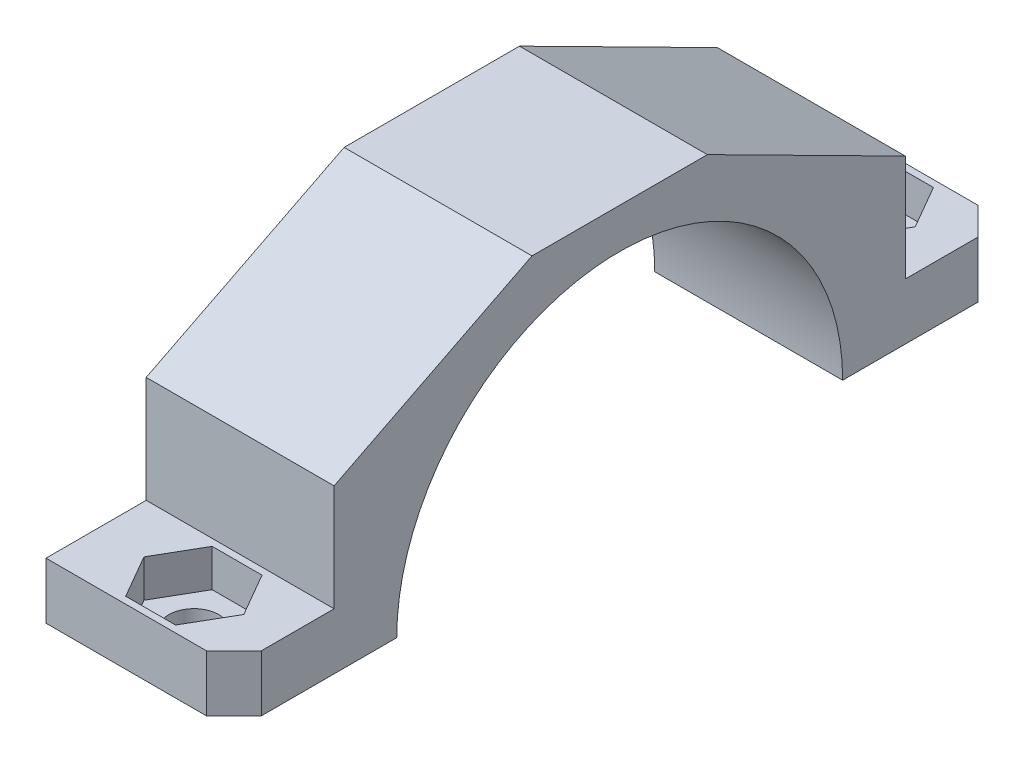
SolidWorks part; units mm, degrees
ref_plane "Front Plane" through (0, 0, 0) normal (0, 0, 1) x (1, 0, 0)
ref_plane "Top Plane" through (0, 0, 0) normal (0, 1, 0) x (1, 0, 0)
ref_plane "Right Plane" through (0, 0, 0) normal (1, 0, 0) x (0, 0, -1)
sketch "Sketch1" plane through (0, 0, 0) normal (1, 0, 0) x (0, 0, -1)
  line L0 (-22.8, 4.5) -> (-22.8, 13)
  line L1 (-22.8, 13) -> (-7, 21)
  line L2 (-7, 21) -> (7, 21)
  line L3 (7, 21) -> (22.8, 13)
  line L4 (22.8, 13) -> (22.8, 4.5)
  line L5 (-30.8, 0) -> (-17.8, 0)
  line L11 (17.8, 0) -> (30.8, 0)
  line L13 (-30.8, 0) -> (-30.8, 4.5)
  line L14 (-30.8, 4.5) -> (-22.8, 4.5)
  line L15 (22.8, 4.5) -> (30.8, 4.5)
  line L16 (30.8, 4.5) -> (30.8, 0)
  arc A0 (-17.8, 0) -> (17.8, 0) centre (0, 0) cw
  point P6 (0, 21)
  dimension "D2" = 17.8
  dimension "D1" = 61.6
  dimension "D3" = 8
  dimension "D4" = 8
  dimension "D5" = 21
  dimension "D6" = 13
  dimension "D7" = 30.8
  dimension "D8" = 4.5
  dimension "D9" = 14
extrude "Boss-Extrude1" add sketch "Sketch1" along normal mid plane 15
sketch "Sketch2" plane through (0, 0, 0) normal (0, -1, 0) x (1, 0, 0)
  line L0 (5.3052, -30.8) -> (7.5, -28.6052)
  line L1 (7.5, -30.8) -> (-7.5, -30.8) construction
  line L2 (5.3052, -30.8) -> (12.8052, -23.3) construction
  line L3 (7.5, -17.8) -> (7.5, -30.8) construction
  line L4 (7.5, -28.6052) -> (7.5, -30.8)
  line L5 (7.5, -30.8) -> (5.3052, -30.8)
  line L6 (5.3052, 30.8) -> (7.5, 28.6052)
  line L7 (7.5, 30.8) -> (-7.5, 30.8) construction
  line L8 (7.5, 30.8) -> (7.5, 17.8) construction
  line L9 (12.8052, 23.3) -> (5.3052, 30.8) construction
  line L10 (7.5, 28.6052) -> (7.5, 30.8)
  line L11 (7.5, 30.8) -> (5.3052, 30.8)
extrude "Cut-Extrude1" cut sketch "Sketch2" against normal through all
hole_wizard "CSK for M4 SFHCS1" positions "Sketch3" profile "Sketch4" countersink size "M4" standard "ANSI Metric"
sketch "Sketch3" plane through (-1355.266, -21, 695.683) normal (0, -1, 0) x (0, 0, -1)
  point P0 (668.883, 1355.5712)
  point P2 (668.883, 1318.5712)
  point P4 (722.483, 1318.5712)
  point P6 (722.483, 1355.5712)
sketch "Sketch4" plane through (0.3052, -21, 26.8) normal (1, 0, 0) x (0, 0, -1)
  line L0 (0, 0) -> (0, 26.7017)
  line L1 (0, 26.7017) -> (2, 25.5)
  line L2 (2, 25.5) -> (2, 1.8)
  line L3 (2, 1.8) -> (3.8, 0)
  line L4 (3.8, 0) -> (0, 0)
  line L5 (-2, 1.8) -> (-3.8, 0) construction
  line L6 (0, 26.7017) -> (-2, 25.5) construction
  line L7 (0, -6.35) -> (0, 107.95) construction
  dimension "Hole Dia." = 4
  dimension "Hole Depth" = 25.5
  dimension "Near C'Sink Dia." = 7.6
  dimension "Near C'Sink Angle" = 90
  dimension "Drill Angle" = 118
sketch "Sketch5" plane through (0, 4.5, 0) normal (0, 1, 0) x (1, 0, 0)
  line L1 (-3.6785, -26.8) -> (-1.6866, -30.25)
  line L2 (-1.6866, -30.25) -> (2.2971, -30.25)
  line L3 (2.2971, -30.25) -> (4.289, -26.8)
  line L4 (4.289, -26.8) -> (2.2971, -23.35)
  line L5 (2.2971, -23.35) -> (-1.6866, -23.35)
  line L6 (-1.6866, -23.35) -> (-3.6785, -26.8)
  line L7 (-3.6785, 26.8) -> (-1.6866, 23.35)
  line L8 (-1.6866, 23.35) -> (2.2971, 23.35)
  line L9 (2.2971, 23.35) -> (4.289, 26.8)
  line L10 (4.289, 26.8) -> (2.2971, 30.25)
  line L11 (2.2971, 30.25) -> (-1.6866, 30.25)
  line L12 (-1.6866, 30.25) -> (-3.6785, 26.8)
  line L13 (5.3052, -30.8) -> (-7.5, -30.8) construction
  line L14 (5.3052, 30.8) -> (-7.5, 30.8) construction
  circle A0 centre (0.3052, -26.8) radius 3.45 construction
  circle A1 centre (0.3052, 26.8) radius 3.45 construction
  dimension "D1" = 6.9
  dimension "D2" = 6.9
extrude "Cut-Extrude2" cut sketch "Sketch5" against normal blind 3
